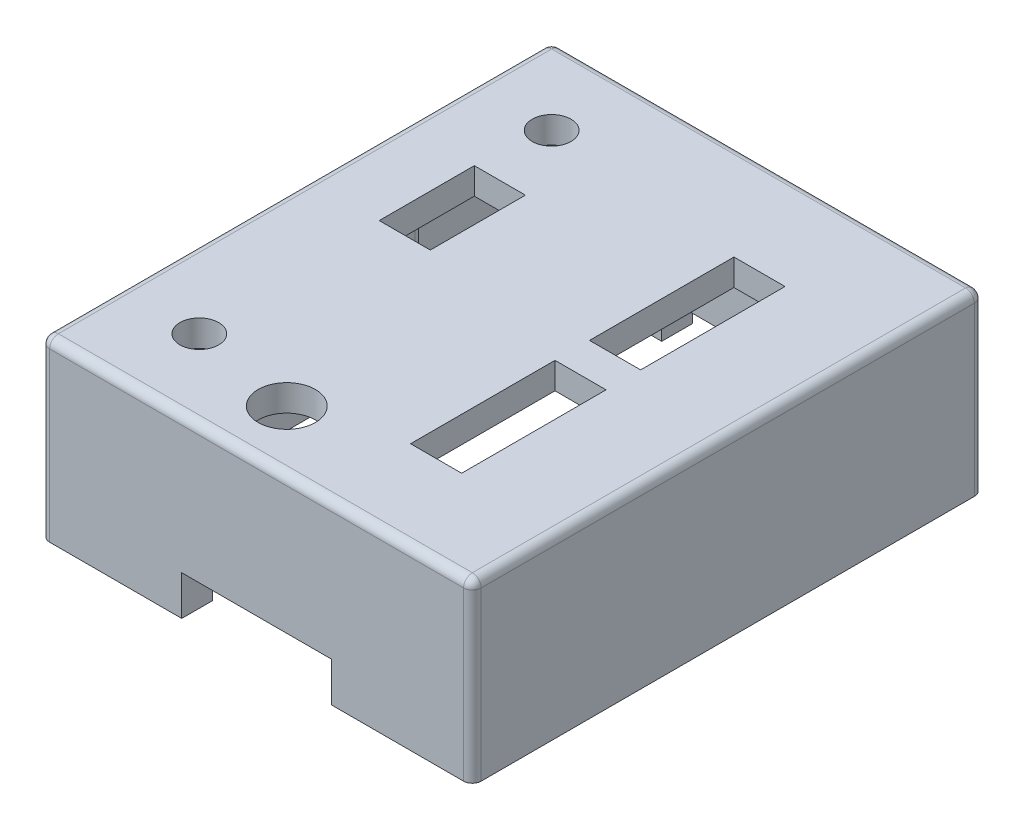
SolidWorks part; units mm, degrees
ref_plane "Front Plane" through (0, 0, 0) normal (0, 0, 1) x (1, 0, 0)
ref_plane "Top Plane" through (0, 0, 0) normal (0, 1, 0) x (1, 0, 0)
ref_plane "Right Plane" through (0, 0, 0) normal (1, 0, 0) x (0, 0, -1)
sketch "Sketch1" plane through (0, 0, 0) normal (0, 1, 0) x (1, 0, 0)
  line L0 (-15.2941, 0) -> (15.2941, 0) construction
  line L1 (-10.25, -12.5) -> (10.25, -12.5) construction
  line L2 (-10.25, -12.5) -> (-10.25, 12.5) construction
  line L3 (-10.25, 12.5) -> (10.25, 12.5) construction
  line L4 (10.25, -12.5) -> (10.25, 12.5) construction
  line L5 (-10.25, -12.5) -> (10.25, 12.5) construction
  line L6 (-10.25, 12.5) -> (10.25, -12.5) construction
  line L7 (0, 17.7941) -> (0, -15.2451) construction
  line L9 (3.6542, 0.7468) -> (6.5542, 0.7468) construction
  line L10 (3.6542, 0.7468) -> (3.6542, 8.9468) construction
  line L11 (3.6542, 8.9468) -> (6.5542, 8.9468) construction
  line L12 (6.5542, 0.7468) -> (6.5542, 8.9468) construction
  line L13 (3.6542, 0.7468) -> (6.5542, 8.9468) construction
  line L14 (3.6542, 8.9468) -> (6.5542, 0.7468) construction
  line L15 (3.6542, -9.4132) -> (6.5542, -9.4132) construction
  line L16 (3.6542, -9.4132) -> (3.6542, -1.2132) construction
  line L17 (3.6542, -1.2132) -> (6.5542, -1.2132) construction
  line L18 (6.5542, -9.4132) -> (6.5542, -1.2132) construction
  line L19 (3.6542, -9.4132) -> (6.5542, -1.2132) construction
  line L20 (3.6542, -1.2132) -> (6.5542, -9.4132) construction
  line L21 (-8.2076, 0.6688) -> (-5.3076, 0.6688) construction
  line L22 (-8.2076, 0.6688) -> (-8.2076, 6.0688) construction
  line L23 (-8.2076, 6.0688) -> (-5.3076, 6.0688) construction
  line L24 (-5.3076, 0.6688) -> (-5.3076, 6.0688) construction
  line L25 (-8.2076, 0.6688) -> (-5.3076, 6.0688) construction
  line L26 (-8.2076, 6.0688) -> (-5.3076, 0.6688) construction
  circle A0 centre (-7.75, 10) radius 1.1 construction
  circle A1 centre (-7.75, -10) radius 1.1 construction
  point P0 (0, 0)
  point P14 (5.1042, 4.8468)
  point P19 (5.1042, -5.3132)
  point P25 (-6.7576, 3.3688)
  point P32 (-1.7156, -11.0712)
  dimension "D5" = 2.2
  dimension "D1" = 25
  dimension "D2" = 20.5
  dimension "D3" = 2.5
  dimension "D4" = 2.5
  dimension "D6" = 8.2
  dimension "D7" = 2.9
  dimension "D8" = 7.6532
  dimension "D9" = 15.3542
  dimension "D10" = 17.8132
  dimension "D11" = 5.4
  dimension "D12" = 3.4924
  dimension "D13" = 9.1312
  dimension "D14" = 8.5344
  dimension "D15" = 23.5712
sketch "Sketch2" plane through (0, 0, 0) normal (0, 1, 0) x (1, 0, 0)
  line L0 (-12.25, 14.5) -> (12.25, 14.5)
  line L5 (-10.25, -12.5) -> (10.25, 12.5) construction
  line L6 (-10.25, 12.5) -> (10.25, -12.5) construction
  line L7 (12.25, -14.5) -> (12.25, 14.5)
  line L8 (-12.25, -14.5) -> (12.25, -14.5)
  line L9 (-12.25, -14.5) -> (-12.25, 14.5)
  point P0 (0, 0)
extrude "Boss-Extrude1" add sketch "Sketch2" against normal blind 10
sketch "Sketch3" plane through (0, -10, 0) normal (0, -1, 0) x (1, 0, 0)
  line L0 (-10.5, 12.75) -> (10.5, 12.75)
  line L5 (-10.25, -12.5) -> (10.25, 12.5) construction
  line L6 (-10.25, 12.5) -> (10.25, -12.5) construction
  line L7 (10.5, -12.75) -> (10.5, 12.75)
  line L8 (-10.5, -12.75) -> (10.5, -12.75)
  line L9 (-10.5, -12.75) -> (-10.5, 12.75)
  point P0 (0, 0)
extrude "Cut-Extrude1" cut sketch "Sketch3" against normal blind 8.5
sketch "Sketch4" plane through (0, 0, 0) normal (0, 1, 0) x (1, 0, 0)
  line L1 (-8.2076, 0.6688) -> (-5.3076, 0.6688)
  line L2 (-8.2076, 0.6688) -> (-8.2076, 6.0688)
  line L3 (-8.2076, 6.0688) -> (-5.3076, 6.0688)
  line L4 (-5.3076, 0.6688) -> (-5.3076, 6.0688)
  line L5 (-8.2076, 0.6688) -> (-5.3076, 6.0688) construction
  line L6 (-8.2076, 6.0688) -> (-5.3076, 0.6688) construction
  line L7 (3.6542, 0.7468) -> (6.5542, 0.7468)
  line L8 (3.6542, 0.7468) -> (3.6542, 8.9468)
  line L9 (3.6542, 8.9468) -> (6.5542, 8.9468)
  line L10 (6.5542, 0.7468) -> (6.5542, 8.9468)
  line L11 (3.6542, 0.7468) -> (6.5542, 8.9468) construction
  line L12 (3.6542, 8.9468) -> (6.5542, 0.7468) construction
  line L13 (3.6542, -9.4132) -> (6.5542, -9.4132)
  line L14 (3.6542, -9.4132) -> (3.6542, -1.2132)
  line L15 (3.6542, -1.2132) -> (6.5542, -1.2132)
  line L16 (6.5542, -9.4132) -> (6.5542, -1.2132)
  line L17 (3.6542, -9.4132) -> (6.5542, -1.2132) construction
  line L18 (3.6542, -1.2132) -> (6.5542, -9.4132) construction
  circle A0 centre (-7.75, -10) radius 1.1
  circle A1 centre (-7.75, 10) radius 1.1
  circle A2 centre (-1.7156, -11.0712) radius 1.625
  point P0 (-6.7576, 3.3688)
  point P7 (5.1042, 4.8468)
  point P14 (5.1042, -5.3132)
  dimension "D1" = 3.25
extrude "Cut-Extrude2" cut sketch "Sketch4" against normal through all
sketch "Sketch5" plane through (0, 0, 14.5) normal (0, 0, 1) x (1, 0, 0)
  line L0 (0, 6.5603) -> (0, -16.4986) construction
  line L1 (-12.25, -10) -> (12.25, -10) construction
  line L2 (4.25, -7.75) -> (-4.25, -7.75)
  line L3 (4.25, -7.75) -> (4.25, -10)
  line L4 (4.25, -10) -> (-4.25, -10)
  line L5 (-4.25, -7.75) -> (-4.25, -10)
  line L6 (4.25, -7.75) -> (-4.25, -10) construction
  line L7 (4.25, -10) -> (-4.25, -7.75) construction
  point P3 (0, -8.875)
  dimension "D1" = 2.25
  dimension "D2" = 8.5
extrude "Cut-Extrude3" cut sketch "Sketch5" against normal through all
fillet "Fillet1" radius 0.5 8 edges at (-12.25, -5, -14.5) (0, 0, 14.5) (-12.25, -5, 14.5) (-12.25, 0, 0) (0, 0, -14.5) (12.25, 0, 0) (12.25, -5, -14.5) (12.25, -5, 14.5)
sketch "Sketch6" plane through (0, -1.5, 0) normal (0, -1, 0) x (1, 0, 0)
  line L0 (-10.5, 12.75) -> (-10.5, -12.75) construction
  line L1 (-10.5, -2) -> (-9, -2)
  line L2 (-10.5, -2) -> (-10.5, -4)
  line L3 (-10.5, -4) -> (-9, -4)
  line L4 (-9, -2) -> (-9, -4)
  line L5 (-15.2941, 0) -> (15.2941, 0) construction
  line L6 (10.5, -12.75) -> (10.5, 12.75) construction
  line L7 (10.5, 7.5) -> (9, 7.5)
  line L8 (10.5, 7.5) -> (10.5, 5.5)
  line L9 (10.5, 5.5) -> (9, 5.5)
  line L10 (9, 7.5) -> (9, 5.5)
  line L12 (10.5, -4.5) -> (9, -4.5)
  line L13 (10.5, -4.5) -> (10.5, -6.5)
  line L14 (10.5, -6.5) -> (9, -6.5)
  line L15 (9, -4.5) -> (9, -6.5)
  dimension "D1" = 2
  dimension "D2" = 1.5
  dimension "D3" = 2
  dimension "D4" = 5.5
  dimension "D5" = 4.5
extrude "Boss-Extrude2" add sketch "Sketch6" along normal blind 2.7
fillet "Fillet2" radius 0.5 21 edges at (-9.75, -1.5, -2) (9.75, -1.5, -6.5) (9.75, -1.5, 5.5) (-9, -1.5, -3) (9, -1.5, -5.5) (9, -1.5, 6.5) (-9.75, -1.5, -4) (-10.5, -2.85, -4) (-9, -2.85, -4) (-9, -2.85, -2) (-10.5, -2.85, -2) (9.75, -1.5, -4.5) (10.5, -2.85, -4.5) (9, -2.85, -4.5) (9, -2.85, -6.5) (10.5, -2.85, -6.5) (9.75, -1.5, 7.5) (10.5, -2.85, 7.5) (9, -2.85, 7.5) (9, -2.85, 5.5) (10.5, -2.85, 5.5)
